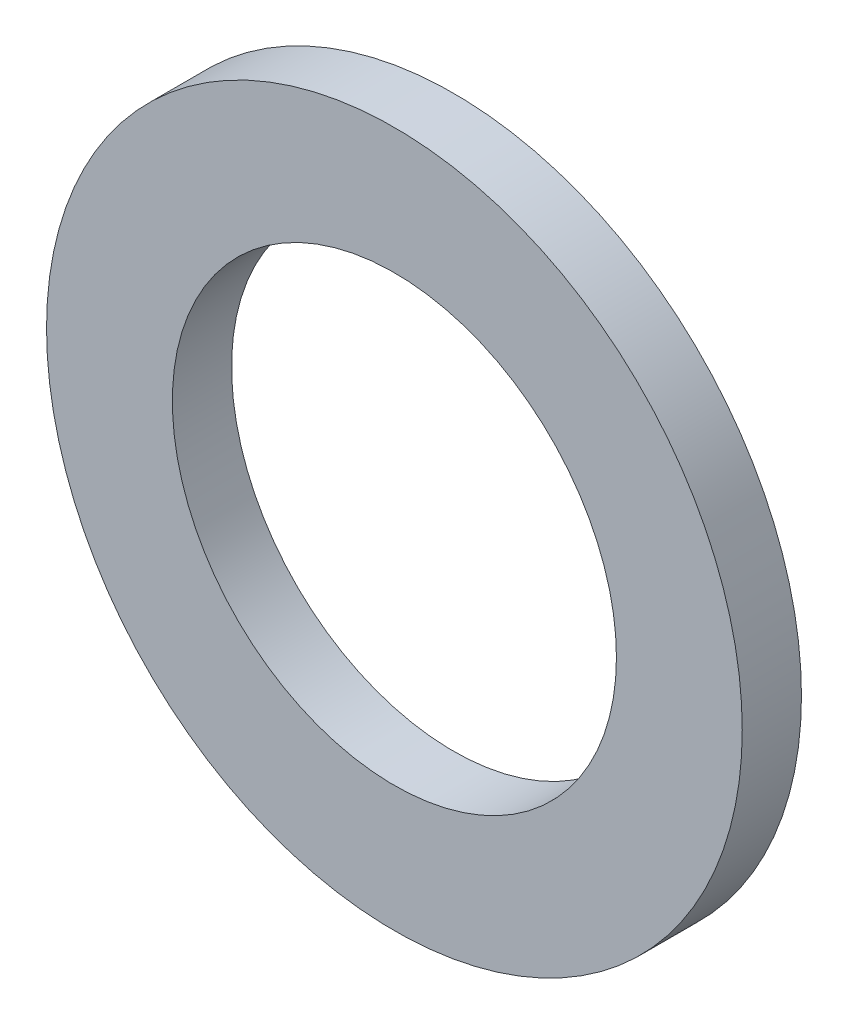
SolidWorks part; units mm, degrees
ref_plane "前视基准面" through (0, 0, 0) normal (0, 0, 1) x (1, 0, 0)
ref_plane "上视基准面" through (0, 0, 0) normal (0, 1, 0) x (1, 0, 0)
ref_plane "右视基准面" through (0, 0, 0) normal (1, 0, 0) x (0, 0, -1)
other "Configuration Table"
sketch "草图1" plane through (0, 0, 0) normal (0, 0, 1) x (1, 0, 0)
  circle A0 centre (0, 0) radius 23.5
  circle A1 centre (0, 0) radius 15
  dimension "D1" = 30
  dimension "D2" = 47
extrude "凸台-拉伸1" add sketch "草图1" along normal blind 4
